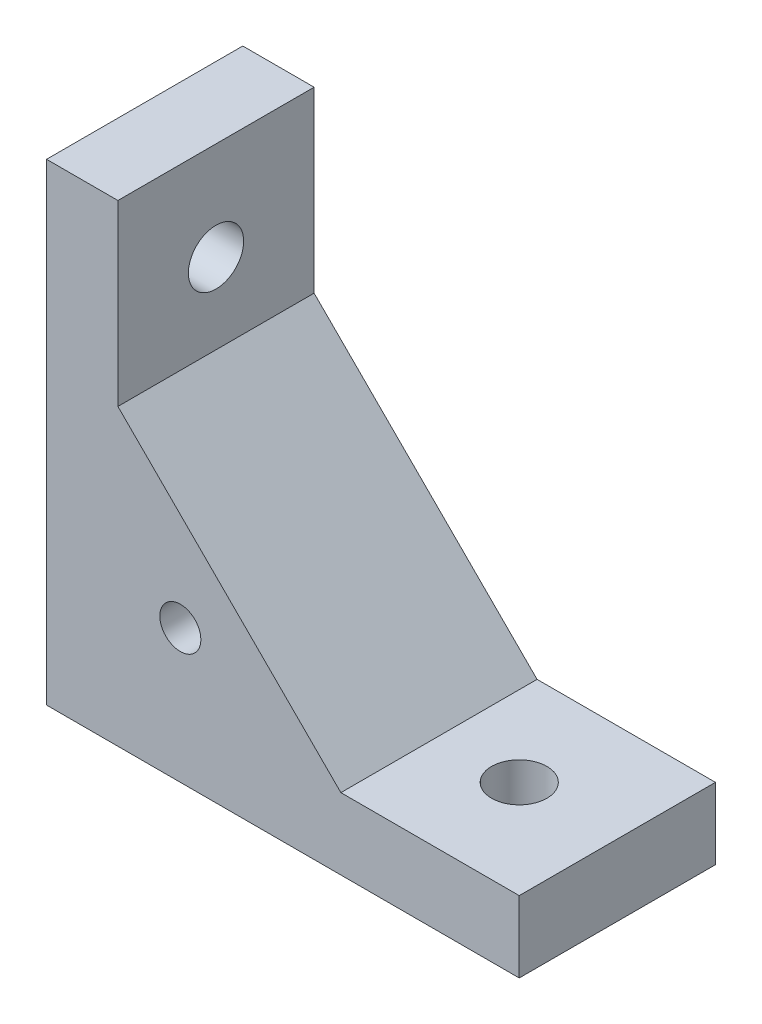
SolidWorks part; units mm, degrees
ref_plane "前视基准面" through (0, 0, 0) normal (0, 0, 1) x (1, 0, 0)
ref_plane "上视基准面" through (0, 0, 0) normal (0, 1, 0) x (1, 0, 0)
ref_plane "右视基准面" through (0, 0, 0) normal (1, 0, 0) x (0, 0, -1)
sketch "草图1" plane through (0, 0, 0) normal (0, 0, 1) x (1, 0, 0)
  line L0 (0, 0) -> (0, 53)
  line L1 (0, 53) -> (8, 53)
  line L2 (8, 53) -> (8, 33)
  line L3 (8, 33) -> (33, 8)
  line L4 (33, 8) -> (53, 8)
  line L5 (53, 8) -> (53, 0)
  line L6 (53, 0) -> (0, 0)
  circle A0 centre (15, 15) radius 2.3
  point P10 (10.9386, 14.2053)
  dimension "D6" = 4.6
  dimension "D1" = 53
  dimension "D2" = 8
  dimension "D3" = 20
  dimension "D4" = 15
  dimension "D5" = 15
extrude "凸台-拉伸1" add sketch "草图1" along normal mid plane 22
hole_wizard "Ø6.2 (6.2) 直径孔1" positions "草图2" profile "草图3" hole size "Ø6.2" standard "ANSI Metric" end condition through all
sketch "草图2" plane through (0, 8, 0) normal (0, 1, 0) x (1, 0, 0)
  line L0 (42, 0) -> (53, 0)
  line L1 (53, -11) -> (53, 11) construction
  point P0 (42, 0)
  dimension "D1" = 11
sketch "草图3" plane through (42, 8, 0) normal (1, 0, 0) x (0, 0, 1)
  line L0 (0, 0) -> (0, 8)
  line L1 (0, 8) -> (3.1, 8)
  line L2 (3.1, 8) -> (3.1, 0)
  line L5 (3.1, 0) -> (0, 0)
  line L11 (0, -6.35) -> (0, 107.95) construction
  dimension "通孔孔直径" = 6.2
  dimension "通孔孔深度" = 8
hole_wizard "Ø6.2 (6.2) 直径孔2" positions "草图4" profile "草图5" hole size "Ø6.2" standard "ANSI Metric" end condition through all
sketch "草图4" plane through (8, 0, 0) normal (1, 0, 0) x (0, 0, -1)
  line L0 (0, 53) -> (0, 42)
  line L1 (-11, 53) -> (11, 53) construction
  point P0 (0, 42)
  dimension "D1" = 11
sketch "草图5" plane through (8, 42, 0) normal (0, 1, 0) x (0, 0, -1)
  line L0 (0, 0) -> (0, 8)
  line L1 (0, 8) -> (3.1, 8)
  line L2 (3.1, 8) -> (3.1, 0)
  line L5 (3.1, 0) -> (0, 0)
  line L11 (0, -6.35) -> (0, 107.95) construction
  dimension "通孔孔直径" = 6.2
  dimension "通孔孔深度" = 8
